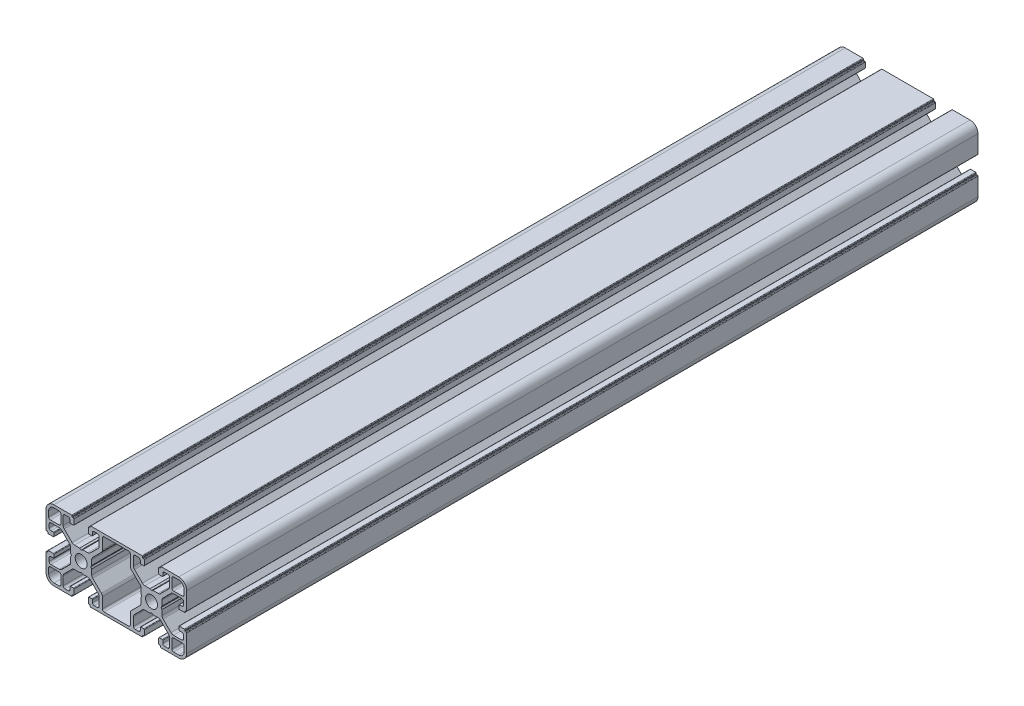
SolidWorks part; units mm, degrees
ref_plane "Front Plane" through (0, 0, 0) normal (0, 0, 1) x (1, 0, 0)
ref_plane "Top Plane" through (0, 0, 0) normal (0, 1, 0) x (1, 0, 0)
ref_plane "Right Plane" through (0, 0, 0) normal (1, 0, 0) x (0, 0, -1)
sketch "Model" plane through (0, 0, 0) normal (0, 0, 1) x (1, 0, 0)
  line L8 (8.5358, 10.05) -> (13.4142, 5.1716)
  line L9 (14, 3.7574) -> (14, 0.866)
  line L10 (13.4142, -5.1716) -> (8.5358, -10.05)
  line L11 (7.95, -11.4642) -> (7.95, -17.5)
  line L12 (6.95, -18.5) -> (-6.95, -18.5)
  line L13 (-7.95, -17.5) -> (-7.95, -11.4642)
  line L14 (-8.5358, -10.05) -> (-13.4142, -5.1716)
  line L15 (-14, -3.7574) -> (-14, -0.866)
  line L16 (-13.4142, 5.1716) -> (-8.5358, 10.05)
  line L17 (-7.95, 11.4642) -> (-7.95, 17.5)
  line L18 (-6.95, 18.5) -> (6.95, 18.5)
  line L19 (7.95, 17.5) -> (7.95, 11.4642)
  line L20 (31.55, -17.5) -> (31.55, -12.55)
  line L21 (32.55, -11.55) -> (37.5, -11.55)
  line L22 (38.5, -12.55) -> (38.5, -15.5)
  line L23 (35.5, -18.5) -> (32.55, -18.5)
  line L24 (32.55, 18.5) -> (35.5, 18.5)
  line L25 (38.5, 15.5) -> (38.5, 12.55)
  line L26 (37.5, 11.55) -> (32.55, 11.55)
  line L27 (31.55, 12.55) -> (31.55, 17.5)
  line L28 (-31.55, 17.5) -> (-31.55, 12.55)
  line L29 (-32.55, 11.55) -> (-37.5, 11.55)
  line L30 (-38.5, 12.55) -> (-38.5, 15.5)
  line L31 (-35.5, 18.5) -> (-32.55, 18.5)
  line L32 (-32.55, -18.5) -> (-35.5, -18.5)
  line L33 (-38.5, -15.5) -> (-38.5, -12.55)
  line L34 (-37.5, -11.55) -> (-32.55, -11.55)
  line L35 (-31.55, -12.55) -> (-31.55, -17.5)
  line L36 (15.6, -19) -> (15.1, -19)
  line L37 (15.9, -15.8) -> (15.9, -18.8)
  line L38 (13.9, -15.5) -> (15.6, -15.5)
  line L39 (13.6, -17.2) -> (13.6, -15.8)
  line L40 (10.75, -18.2) -> (12.6, -18.2)
  line L41 (9.75, -12.4926) -> (9.75, -17.2)
  line L42 (14.8284, -6.5858) -> (10.3358, -11.0784)
  line L43 (23.7574, -6) -> (20.866, -6)
  line L44 (29.6642, -11.0784) -> (25.1716, -6.5858)
  line L45 (30.25, -17.2) -> (30.25, -12.4926)
  line L46 (27.4, -18.2) -> (29.25, -18.2)
  line L47 (26.4, -15.8) -> (26.4, -17.2)
  line L48 (24.4, -15.5) -> (26.1, -15.5)
  line L49 (24.1, -18.8) -> (24.1, -15.8)
  line L50 (24.9, -19) -> (24.4, -19)
  line L51 (25.1, -19.7) -> (25.1, -19.2)
  line L52 (35.5, -20) -> (25.4, -20)
  line L53 (40, -5.4) -> (40, -15.5)
  line L54 (39.2, -5.1) -> (39.7, -5.1)
  line L55 (39, -4.4) -> (39, -4.9)
  line L56 (35.8, -4.1) -> (38.7, -4.1)
  line L57 (35.5, -6.1) -> (35.5, -4.4)
  line L58 (37.2, -6.4) -> (35.8, -6.4)
  line L59 (38.2, -9.25) -> (38.2, -7.4)
  line L60 (32.4926, -10.25) -> (37.2, -10.25)
  line L61 (26.5858, -5.1716) -> (31.0784, -9.6642)
  line L62 (26, 3.7574) -> (26, 0.866)
  line L63 (31.0784, 9.6642) -> (26.5858, 5.1716)
  line L64 (37.2, 10.25) -> (32.4926, 10.25)
  line L65 (38.2, 7.4) -> (38.2, 9.25)
  line L66 (35.8, 6.4) -> (37.2, 6.4)
  line L67 (35.5, 4.4) -> (35.5, 6.1)
  line L68 (38.7, 4.1) -> (35.8, 4.1)
  line L69 (39, 4.9) -> (39, 4.4)
  line L70 (39.7, 5.1) -> (39.2, 5.1)
  line L71 (40, 15.5) -> (40, 5.4)
  line L72 (25.4, 20) -> (35.5, 20)
  line L73 (25.1, 19.2) -> (25.1, 19.7)
  line L74 (24.4, 19) -> (24.9, 19)
  line L75 (24.1, 15.8) -> (24.1, 18.7)
  line L76 (26.1, 15.5) -> (24.4, 15.5)
  line L77 (26.4, 17.2) -> (26.4, 15.8)
  line L78 (29.25, 18.2) -> (27.4, 18.2)
  line L79 (30.25, 12.4926) -> (30.25, 17.2)
  line L80 (25.1716, 6.5858) -> (29.6642, 11.0784)
  line L81 (16.2426, 6) -> (19.134, 6)
  line L82 (10.3358, 11.0784) -> (14.8284, 6.5858)
  line L83 (9.75, 17.2) -> (9.75, 12.4926)
  line L84 (12.6, 18.2) -> (10.75, 18.2)
  line L85 (13.6, 15.8) -> (13.6, 17.2)
  line L86 (15.6, 15.5) -> (13.9, 15.5)
  line L87 (15.9, 18.7) -> (15.9, 15.8)
  line L88 (15.1, 19) -> (15.6, 19)
  line L89 (14.9, 19.7) -> (14.9, 19.2)
  line L90 (14.6, 20) -> (-14.6, 20)
  line L91 (-14.9, 19.7) -> (-14.9, 19.2)
  line L92 (-15.1, 19) -> (-15.6, 19)
  line L93 (-15.9, 18.7) -> (-15.9, 15.8)
  line L94 (-15.6, 15.5) -> (-13.9, 15.5)
  line L95 (-13.6, 15.8) -> (-13.6, 17.2)
  line L96 (-12.6, 18.2) -> (-10.75, 18.2)
  line L97 (-9.75, 17.2) -> (-9.75, 12.4926)
  line L98 (-10.3358, 11.0784) -> (-14.8284, 6.5858)
  line L99 (-16.2426, 6) -> (-19.134, 6)
  line L100 (-25.1716, 6.5858) -> (-29.6642, 11.0784)
  line L101 (-30.25, 12.4926) -> (-30.25, 17.2)
  line L102 (-29.25, 18.2) -> (-27.4, 18.2)
  line L103 (-26.4, 17.2) -> (-26.4, 15.8)
  line L104 (-26.1, 15.5) -> (-24.4, 15.5)
  line L105 (-24.1, 15.8) -> (-24.1, 18.7)
  line L106 (-24.4, 19) -> (-24.9, 19)
  line L107 (-25.1, 19.2) -> (-25.1, 19.7)
  line L108 (-25.4, 20) -> (-35.5, 20)
  line L109 (-40, 15.5) -> (-40, 5.4)
  line L110 (-39.7, 5.1) -> (-39.2, 5.1)
  line L111 (-39, 4.9) -> (-39, 4.4)
  line L112 (-38.7, 4.1) -> (-35.8, 4.1)
  line L113 (-35.5, 4.4) -> (-35.5, 6.1)
  line L114 (-35.8, 6.4) -> (-37.2, 6.4)
  line L115 (-38.2, 7.4) -> (-38.2, 9.25)
  line L116 (-37.2, 10.25) -> (-32.4926, 10.25)
  line L117 (-31.0784, 9.6642) -> (-26.5858, 5.1716)
  line L118 (-26, 3.7574) -> (-26, 0.866)
  line L119 (-26.5858, -5.1716) -> (-31.0784, -9.6642)
  line L120 (-32.4926, -10.25) -> (-37.2, -10.25)
  line L121 (-38.2, -9.25) -> (-38.2, -7.4)
  line L122 (-37.2, -6.4) -> (-35.8, -6.4)
  line L123 (-35.5, -6.1) -> (-35.5, -4.4)
  line L124 (-35.8, -4.1) -> (-38.7, -4.1)
  line L125 (-39, -4.4) -> (-39, -4.9)
  line L126 (-39.2, -5.1) -> (-39.7, -5.1)
  line L127 (-40, -5.4) -> (-40, -15.5)
  line L128 (-35.5, -20) -> (-25.4, -20)
  line L129 (-25.1, -19.7) -> (-25.1, -19.2)
  line L130 (-24.9, -19) -> (-24.4, -19)
  line L131 (-24.1, -18.8) -> (-24.1, -15.8)
  line L132 (-24.4, -15.5) -> (-26.1, -15.5)
  line L133 (-26.4, -15.8) -> (-26.4, -17.2)
  line L134 (-27.4, -18.2) -> (-29.25, -18.2)
  line L135 (-30.25, -17.2) -> (-30.25, -12.4926)
  line L136 (-29.6642, -11.0784) -> (-25.1716, -6.5858)
  line L137 (-23.7574, -6) -> (-20.866, -6)
  line L138 (-14.8284, -6.5858) -> (-10.3358, -11.0784)
  line L139 (-9.75, -12.4926) -> (-9.75, -17.2)
  line L140 (-10.75, -18.2) -> (-12.6, -18.2)
  line L141 (-13.6, -17.2) -> (-13.6, -15.8)
  line L142 (-13.9, -15.5) -> (-15.6, -15.5)
  line L143 (-15.9, -15.8) -> (-15.9, -18.8)
  line L144 (-15.6, -19) -> (-15.1, -19)
  line L145 (-14.9, -19.2) -> (-14.9, -19.7)
  line L146 (14.6, -20) -> (-14.6, -20)
  line L147 (14.9, -19.2) -> (14.9, -19.7)
  line L148 (-25.5, 0) -> (-26, 0.866)
  line L149 (-25.5, 0) -> (-26, -0.866)
  line L150 (-26, -0.866) -> (-26, -3.7574)
  line L151 (-20, -5.5) -> (-20.866, -6)
  line L152 (-20, -5.5) -> (-19.134, -6)
  line L153 (-14.5, 0) -> (-14, -0.866)
  line L154 (-14.5, 0) -> (-14, 0.866)
  line L155 (-20, 5.5) -> (-19.134, 6)
  line L156 (-20, 5.5) -> (-20.866, 6)
  line L157 (-20.866, 6) -> (-23.7574, 6)
  line L158 (-14, 0.866) -> (-14, 3.7574)
  line L159 (-19.134, -6) -> (-16.2426, -6)
  line L160 (14.5, 0) -> (14, 0.866)
  line L161 (14.5, 0) -> (14, -0.866)
  line L162 (20, -5.5) -> (19.134, -6)
  line L163 (20, -5.5) -> (20.866, -6)
  line L164 (25.5, 0) -> (26, -0.866)
  line L165 (25.5, 0) -> (26, 0.866)
  line L166 (20, 5.5) -> (20.866, 6)
  line L167 (20, 5.5) -> (19.134, 6)
  line L168 (26, -0.866) -> (26, -3.7574)
  line L169 (20.866, 6) -> (23.7574, 6)
  line L170 (14, -0.866) -> (14, -3.7574)
  line L171 (19.134, -6) -> (16.2426, -6)
  circle A0 centre (-20, 0) radius 3.4
  arc A1 (7.95, 11.4642) -> (8.5358, 10.05) centre (9.95, 11.4642) ccw
  arc A2 (14, 3.7574) -> (13.4142, 5.1716) centre (12, 3.7574) ccw
  arc A3 (13.4142, -5.1716) -> (14, -3.7574) centre (12, -3.7574) ccw
  arc A4 (8.5358, -10.05) -> (7.95, -11.4642) centre (9.95, -11.4642) ccw
  arc A5 (6.95, -18.5) -> (7.95, -17.5) centre (6.95, -17.5) ccw
  arc A6 (-7.95, -17.5) -> (-6.95, -18.5) centre (-6.95, -17.5) ccw
  arc A7 (-7.95, -11.4642) -> (-8.5358, -10.05) centre (-9.95, -11.4642) ccw
  arc A8 (-14, -3.7574) -> (-13.4142, -5.1716) centre (-12, -3.7574) ccw
  arc A9 (-13.4142, 5.1716) -> (-14, 3.7574) centre (-12, 3.7574) ccw
  arc A10 (-8.5358, 10.05) -> (-7.95, 11.4642) centre (-9.95, 11.4642) ccw
  arc A11 (-6.95, 18.5) -> (-7.95, 17.5) centre (-6.95, 17.5) ccw
  arc A12 (7.95, 17.5) -> (6.95, 18.5) centre (6.95, 17.5) ccw
  circle A13 centre (20, 0) radius 3.4
  arc A14 (31.55, -17.5) -> (32.55, -18.5) centre (32.55, -17.5) ccw
  arc A15 (32.55, -11.55) -> (31.55, -12.55) centre (32.55, -12.55) ccw
  arc A16 (38.5, -12.55) -> (37.5, -11.55) centre (37.5, -12.55) ccw
  arc A17 (35.5, -18.5) -> (38.5, -15.5) centre (35.5, -15.5) ccw
  arc A18 (32.55, 18.5) -> (31.55, 17.5) centre (32.55, 17.5) ccw
  arc A19 (38.5, 15.5) -> (35.5, 18.5) centre (35.5, 15.5) ccw
  arc A20 (37.5, 11.55) -> (38.5, 12.55) centre (37.5, 12.55) ccw
  arc A21 (31.55, 12.55) -> (32.55, 11.55) centre (32.55, 12.55) ccw
  arc A22 (-31.55, 17.5) -> (-32.55, 18.5) centre (-32.55, 17.5) ccw
  arc A23 (-32.55, 11.55) -> (-31.55, 12.55) centre (-32.55, 12.55) ccw
  arc A24 (-38.5, 12.55) -> (-37.5, 11.55) centre (-37.5, 12.55) ccw
  arc A25 (-35.5, 18.5) -> (-38.5, 15.5) centre (-35.5, 15.5) ccw
  arc A26 (-32.55, -18.5) -> (-31.55, -17.5) centre (-32.55, -17.5) ccw
  arc A27 (-38.5, -15.5) -> (-35.5, -18.5) centre (-35.5, -15.5) ccw
  arc A28 (-37.5, -11.55) -> (-38.5, -12.55) centre (-37.5, -12.55) ccw
  arc A29 (-31.55, -12.55) -> (-32.55, -11.55) centre (-32.55, -12.55) ccw
  arc A30 (15.1, -19) -> (14.9, -19.2) centre (15.1, -19.2) ccw
  arc A31 (15.6, -19) -> (15.9, -18.8) centre (15.6718, -18.7827) ccw
  arc A32 (15.9, -15.8) -> (15.6, -15.5) centre (15.6, -15.8) ccw
  arc A33 (13.9, -15.5) -> (13.6, -15.8) centre (13.9, -15.8) ccw
  arc A34 (12.6, -18.2) -> (13.6, -17.2) centre (12.6, -17.2) ccw
  arc A35 (9.75, -17.2) -> (10.75, -18.2) centre (10.75, -17.2) ccw
  arc A36 (10.3358, -11.0784) -> (9.75, -12.4926) centre (11.75, -12.4926) ccw
  arc A37 (16.2426, -6) -> (14.8284, -6.5858) centre (16.2426, -8) ccw
  arc A38 (25.1716, -6.5858) -> (23.7574, -6) centre (23.7574, -8) ccw
  arc A39 (30.25, -12.4926) -> (29.6642, -11.0784) centre (28.25, -12.4926) ccw
  arc A40 (29.25, -18.2) -> (30.25, -17.2) centre (29.25, -17.2) ccw
  arc A41 (26.4, -17.2) -> (27.4, -18.2) centre (27.4, -17.2) ccw
  arc A42 (26.4, -15.8) -> (26.1, -15.5) centre (26.1, -15.8) ccw
  arc A43 (24.4, -15.5) -> (24.1, -15.8) centre (24.4, -15.8) ccw
  arc A44 (24.1, -18.8) -> (24.4, -19) centre (24.3282, -18.7827) ccw
  arc A45 (25.1, -19.2) -> (24.9, -19) centre (24.9, -19.2) ccw
  arc A46 (25.1, -19.7) -> (25.4, -20) centre (25.4, -19.7) ccw
  arc A47 (35.5, -20) -> (40, -15.5) centre (35.5, -15.5) ccw
  arc A48 (40, -5.4) -> (39.7, -5.1) centre (39.7, -5.4) ccw
  arc A49 (39, -4.9) -> (39.2, -5.1) centre (39.2, -4.9) ccw
  arc A50 (39, -4.4) -> (38.7, -4.1) centre (38.7, -4.4) ccw
  arc A51 (35.8, -4.1) -> (35.5, -4.4) centre (35.8, -4.4) ccw
  arc A52 (35.5, -6.1) -> (35.8, -6.4) centre (35.8, -6.1) ccw
  arc A53 (38.2, -7.4) -> (37.2, -6.4) centre (37.2, -7.4) ccw
  arc A54 (37.2, -10.25) -> (38.2, -9.25) centre (37.2, -9.25) ccw
  arc A55 (31.0784, -9.6642) -> (32.4926, -10.25) centre (32.4926, -8.25) ccw
  arc A56 (26, -3.7574) -> (26.5858, -5.1716) centre (28, -3.7574) ccw
  arc A57 (26.5858, 5.1716) -> (26, 3.7574) centre (28, 3.7574) ccw
  arc A58 (32.4926, 10.25) -> (31.0784, 9.6642) centre (32.4926, 8.25) ccw
  arc A59 (38.2, 9.25) -> (37.2, 10.25) centre (37.2, 9.25) ccw
  arc A60 (37.2, 6.4) -> (38.2, 7.4) centre (37.2, 7.4) ccw
  arc A61 (35.8, 6.4) -> (35.5, 6.1) centre (35.8, 6.1) ccw
  arc A62 (35.5, 4.4) -> (35.8, 4.1) centre (35.8, 4.4) ccw
  arc A63 (38.7, 4.1) -> (39, 4.4) centre (38.7, 4.4) ccw
  arc A64 (39.2, 5.1) -> (39, 4.9) centre (39.2, 4.9) ccw
  arc A65 (39.7, 5.1) -> (40, 5.4) centre (39.7, 5.4) ccw
  arc A66 (40, 15.5) -> (35.5, 20) centre (35.5, 15.5) ccw
  arc A67 (25.4, 20) -> (25.1, 19.7) centre (25.4, 19.7) ccw
  arc A68 (24.9, 19) -> (25.1, 19.2) centre (24.9, 19.2) ccw
  arc A69 (24.4, 19) -> (24.1, 18.7) centre (24.4, 18.7) ccw
  arc A70 (24.1, 15.8) -> (24.4, 15.5) centre (24.4, 15.8) ccw
  arc A71 (26.1, 15.5) -> (26.4, 15.8) centre (26.1, 15.8) ccw
  arc A72 (27.4, 18.2) -> (26.4, 17.2) centre (27.4, 17.2) ccw
  arc A73 (30.25, 17.2) -> (29.25, 18.2) centre (29.25, 17.2) ccw
  arc A74 (29.6642, 11.0784) -> (30.25, 12.4926) centre (28.25, 12.4926) ccw
  arc A75 (23.7574, 6) -> (25.1716, 6.5858) centre (23.7574, 8) ccw
  arc A76 (14.8284, 6.5858) -> (16.2426, 6) centre (16.2426, 8) ccw
  arc A77 (9.75, 12.4926) -> (10.3358, 11.0784) centre (11.75, 12.4926) ccw
  arc A78 (10.75, 18.2) -> (9.75, 17.2) centre (10.75, 17.2) ccw
  arc A79 (13.6, 17.2) -> (12.6, 18.2) centre (12.6, 17.2) ccw
  arc A80 (13.6, 15.8) -> (13.9, 15.5) centre (13.9, 15.8) ccw
  arc A81 (15.6, 15.5) -> (15.9, 15.8) centre (15.6, 15.8) ccw
  arc A82 (15.9, 18.7) -> (15.6, 19) centre (15.6, 18.7) ccw
  arc A83 (14.9, 19.2) -> (15.1, 19) centre (15.1, 19.2) ccw
  arc A84 (14.9, 19.7) -> (14.6, 20) centre (14.6, 19.7) ccw
  arc A85 (-14.6, 20) -> (-14.9, 19.7) centre (-14.6, 19.7) ccw
  arc A86 (-15.1, 19) -> (-14.9, 19.2) centre (-15.1, 19.2) ccw
  arc A87 (-15.6, 19) -> (-15.9, 18.7) centre (-15.6, 18.7) ccw
  arc A88 (-15.9, 15.8) -> (-15.6, 15.5) centre (-15.6, 15.8) ccw
  arc A89 (-13.9, 15.5) -> (-13.6, 15.8) centre (-13.9, 15.8) ccw
  arc A90 (-12.6, 18.2) -> (-13.6, 17.2) centre (-12.6, 17.2) ccw
  arc A91 (-9.75, 17.2) -> (-10.75, 18.2) centre (-10.75, 17.2) ccw
  arc A92 (-10.3358, 11.0784) -> (-9.75, 12.4926) centre (-11.75, 12.4926) ccw
  arc A93 (-16.2426, 6) -> (-14.8284, 6.5858) centre (-16.2426, 8) ccw
  arc A94 (-25.1716, 6.5858) -> (-23.7574, 6) centre (-23.7574, 8) ccw
  arc A95 (-30.25, 12.4926) -> (-29.6642, 11.0784) centre (-28.25, 12.4926) ccw
  arc A96 (-29.25, 18.2) -> (-30.25, 17.2) centre (-29.25, 17.2) ccw
  arc A97 (-26.4, 17.2) -> (-27.4, 18.2) centre (-27.4, 17.2) ccw
  arc A98 (-26.4, 15.8) -> (-26.1, 15.5) centre (-26.1, 15.8) ccw
  arc A99 (-24.4, 15.5) -> (-24.1, 15.8) centre (-24.4, 15.8) ccw
  arc A100 (-24.1, 18.7) -> (-24.4, 19) centre (-24.4, 18.7) ccw
  arc A101 (-25.1, 19.2) -> (-24.9, 19) centre (-24.9, 19.2) ccw
  arc A102 (-25.1, 19.7) -> (-25.4, 20) centre (-25.4, 19.7) ccw
  arc A103 (-35.5, 20) -> (-40, 15.5) centre (-35.5, 15.5) ccw
  arc A104 (-40, 5.4) -> (-39.7, 5.1) centre (-39.7, 5.4) ccw
  arc A105 (-39, 4.9) -> (-39.2, 5.1) centre (-39.2, 4.9) ccw
  arc A106 (-39, 4.4) -> (-38.7, 4.1) centre (-38.7, 4.4) ccw
  arc A107 (-35.8, 4.1) -> (-35.5, 4.4) centre (-35.8, 4.4) ccw
  arc A108 (-35.5, 6.1) -> (-35.8, 6.4) centre (-35.8, 6.1) ccw
  arc A109 (-38.2, 7.4) -> (-37.2, 6.4) centre (-37.2, 7.4) ccw
  arc A110 (-37.2, 10.25) -> (-38.2, 9.25) centre (-37.2, 9.25) ccw
  arc A111 (-31.0784, 9.6642) -> (-32.4926, 10.25) centre (-32.4926, 8.25) ccw
  arc A112 (-26, 3.7574) -> (-26.5858, 5.1716) centre (-28, 3.7574) ccw
  arc A113 (-26.5858, -5.1716) -> (-26, -3.7574) centre (-28, -3.7574) ccw
  arc A114 (-32.4926, -10.25) -> (-31.0784, -9.6642) centre (-32.4926, -8.25) ccw
  arc A115 (-38.2, -9.25) -> (-37.2, -10.25) centre (-37.2, -9.25) ccw
  arc A116 (-37.2, -6.4) -> (-38.2, -7.4) centre (-37.2, -7.4) ccw
  arc A117 (-35.8, -6.4) -> (-35.5, -6.1) centre (-35.8, -6.1) ccw
  arc A118 (-35.5, -4.4) -> (-35.8, -4.1) centre (-35.8, -4.4) ccw
  arc A119 (-38.7, -4.1) -> (-39, -4.4) centre (-38.7, -4.4) ccw
  arc A120 (-39.2, -5.1) -> (-39, -4.9) centre (-39.2, -4.9) ccw
  arc A121 (-39.7, -5.1) -> (-40, -5.4) centre (-39.7, -5.4) ccw
  arc A122 (-40, -15.5) -> (-35.5, -20) centre (-35.5, -15.5) ccw
  arc A123 (-25.4, -20) -> (-25.1, -19.7) centre (-25.4, -19.7) ccw
  arc A124 (-24.9, -19) -> (-25.1, -19.2) centre (-24.9, -19.2) ccw
  arc A125 (-24.4, -19) -> (-24.1, -18.8) centre (-24.3282, -18.7827) ccw
  arc A126 (-24.1, -15.8) -> (-24.4, -15.5) centre (-24.4, -15.8) ccw
  arc A127 (-26.1, -15.5) -> (-26.4, -15.8) centre (-26.1, -15.8) ccw
  arc A128 (-27.4, -18.2) -> (-26.4, -17.2) centre (-27.4, -17.2) ccw
  arc A129 (-30.25, -17.2) -> (-29.25, -18.2) centre (-29.25, -17.2) ccw
  arc A130 (-29.6642, -11.0784) -> (-30.25, -12.4926) centre (-28.25, -12.4926) ccw
  arc A131 (-23.7574, -6) -> (-25.1716, -6.5858) centre (-23.7574, -8) ccw
  arc A132 (-14.8284, -6.5858) -> (-16.2426, -6) centre (-16.2426, -8) ccw
  arc A133 (-9.75, -12.4926) -> (-10.3358, -11.0784) centre (-11.75, -12.4926) ccw
  arc A134 (-10.75, -18.2) -> (-9.75, -17.2) centre (-10.75, -17.2) ccw
  arc A135 (-13.6, -17.2) -> (-12.6, -18.2) centre (-12.6, -17.2) ccw
  arc A136 (-13.6, -15.8) -> (-13.9, -15.5) centre (-13.9, -15.8) ccw
  arc A137 (-15.6, -15.5) -> (-15.9, -15.8) centre (-15.6, -15.8) ccw
  arc A138 (-15.9, -18.8) -> (-15.6, -19) centre (-15.6718, -18.7827) ccw
  arc A139 (-14.9, -19.2) -> (-15.1, -19) centre (-15.1, -19.2) ccw
  arc A140 (-14.9, -19.7) -> (-14.6, -20) centre (-14.6, -19.7) ccw
  arc A141 (14.6, -20) -> (14.9, -19.7) centre (14.6, -19.7) ccw
  point P422 (0, 0)
  dimension "D2" = 6.8
  dimension "D1" = 40
  dimension "D3" = 80
  dimension "D4" = 29.2
extrude "Boss-Extrude1" add sketch "Model" along normal blind 450
